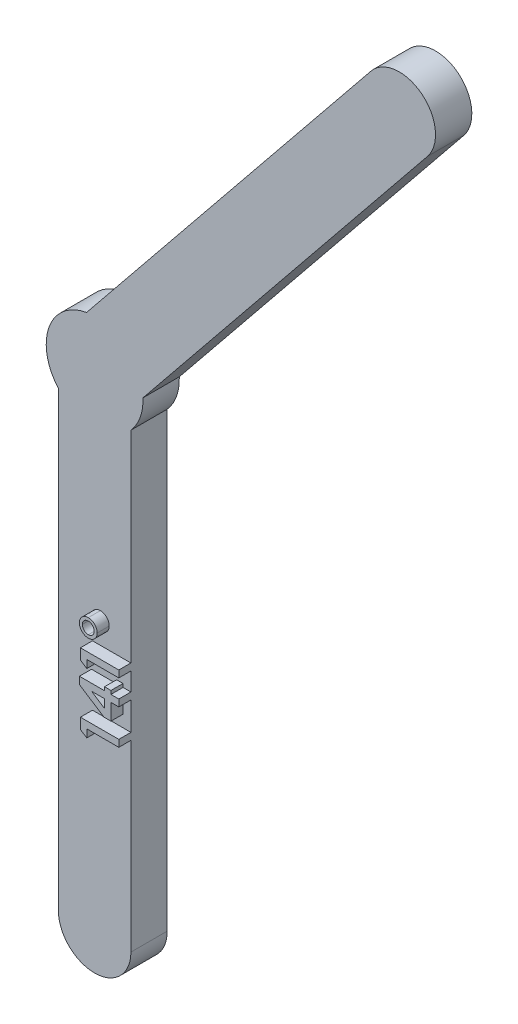
SolidWorks part; units mm, degrees
ref_plane "Front Plane" through (0, 0, 0) normal (0, 0, 1) x (1, 0, 0)
ref_plane "Top Plane" through (0, 0, 0) normal (0, 1, 0) x (1, 0, 0)
ref_plane "Right Plane" through (0, 0, 0) normal (1, 0, 0) x (0, 0, -1)
sketch "Sketch2" plane through (0, 0, 0) normal (0, 0, 1) x (1, 0, 0)
  line L0 (0, 0) -> (0, -40) construction
  line L1 (0, 0) -> (25.1728, 31.0858) construction
  line L2 (22.8414, 32.9738) -> (27.5043, 29.1979) construction
  line L3 (-3, -40) -> (3, -40) construction
  line L4 (-3, -40) -> (-3, -2.6458)
  line L5 (3, -40) -> (3, -2.6458)
  line L6 (22.8414, 32.9738) -> (-0.6664, 3.9441)
  line L7 (27.5043, 29.1979) -> (3.9965, 0.1682)
  arc A0 (-0.6664, 3.9441) -> (-3, -2.6458) centre (0, 0) ccw
  arc A1 (-3, -40) -> (3, -40) centre (0, -40) ccw
  arc A2 (22.8414, 32.9738) -> (27.5043, 29.1979) centre (25.1728, 31.0858) cw
  arc A3 (3, -2.6458) -> (3.9965, 0.1682) centre (0, 0) ccw
  point P12 (25.1728, 31.0858)
  dimension "D3" = 3
  dimension "D4" = 8
  dimension "D1" = 40
  dimension "D2" = 141
extrude "Boss-Extrude1" add sketch "Sketch2" along normal blind 3
sketch "Sketch3" plane through (0, 0, 3) normal (0, 0, 1) x (1, 0, 0)
  text T0 "<b>141°</b>"
extrude "Boss-Extrude2" add sketch "Sketch3" along normal blind 1
